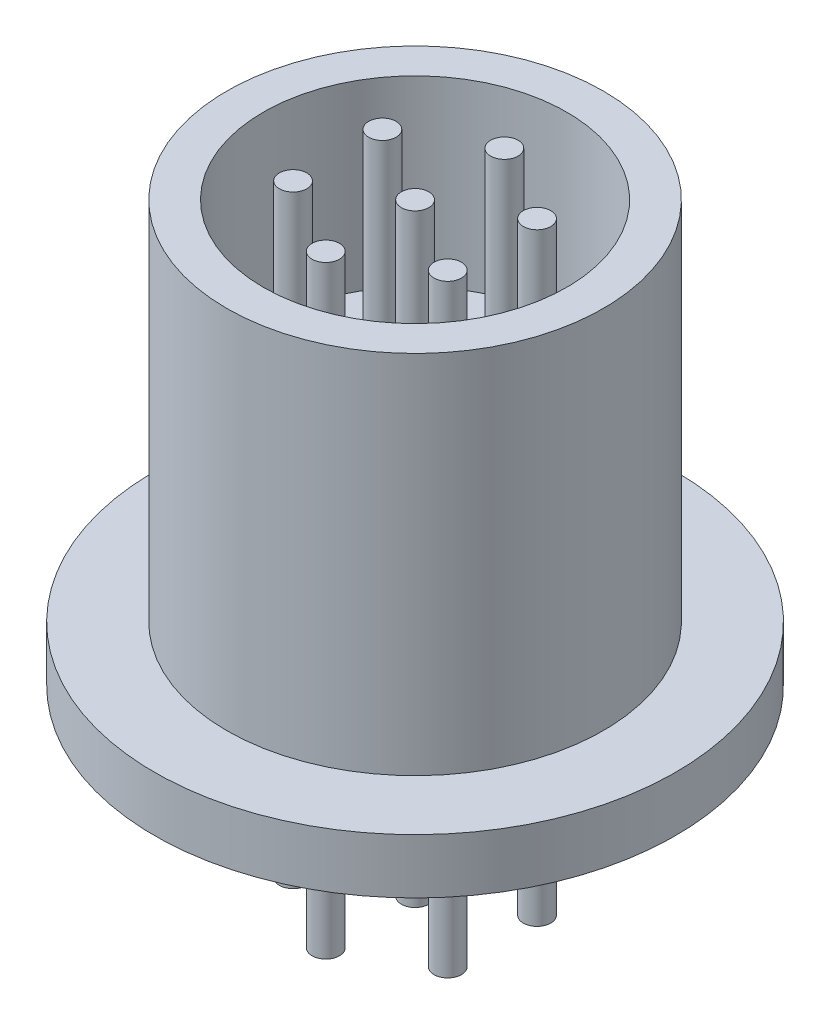
SolidWorks part; units mm, degrees
ref_plane "Front Plane" through (0, 0, 0) normal (0, 0, 1) x (1, 0, 0)
ref_plane "Top Plane" through (0, 0, 0) normal (0, 1, 0) x (1, 0, 0)
ref_plane "Right Plane" through (0, 0, 0) normal (1, 0, 0) x (0, 0, -1)
sketch "Sketch1" plane through (0, 0, 0) normal (0, 1, 0) x (1, 0, 0)
  circle A0 centre (0, 0) radius 10.3
  dimension "D1" = 20.6
extrude "Boss-Extrude1" add sketch "Sketch1" along normal blind 20
sketch "Sketch2" plane through (0, 0, 0) normal (0, -1, 0) x (1, 0, 0)
  circle A0 centre (0, 0) radius 14.25
  dimension "D1" = 28.5
extrude "Boss-Extrude2" add sketch "Sketch2" along normal blind 3
sketch "Sketch3" plane through (0, 20, 0) normal (0, 1, 0) x (1, 0, 0)
  circle A0 centre (0, 0) radius 8.3
  circle A1 centre (0, 0) radius 10.3 construction
  dimension "D1" = 2
extrude "Cut-Extrude1" cut sketch "Sketch3" against normal blind 10
sketch "Sketch4" plane through (0, 10, 0) normal (0, 1, 0) x (1, 0, 0)
  circle A0 centre (0, 4.8844) radius 0.75
  circle A1 centre (4.23, 2.4422) radius 0.75
  circle A2 centre (4.23, -2.4422) radius 0.75
  circle A3 centre (0, -4.8844) radius 0.75
  circle A4 centre (-4.23, -2.4422) radius 0.75
  circle A5 centre (-4.23, 2.4422) radius 0.75
  circle A6 centre (0, 0) radius 0.75
  point P14 (0, 0)
  dimension "D2" = 1.5
  dimension "D1" = 6
extrude "Boss-Extrude3" add sketch "Sketch4" along normal blind 10
sketch "Sketch5" plane through (0, -3, 0) normal (0, -1, 0) x (1, 0, 0)
  circle A1 centre (0, 0) radius 0.75
  circle A2 centre (0, 0) radius 0.75
  circle A3 centre (-4.23, -2.4422) radius 0.75
  circle A4 centre (-4.23, -2.4422) radius 0.75
  circle A5 centre (-4.23, 2.4422) radius 0.75
  circle A6 centre (-4.23, 2.4422) radius 0.75
  circle A7 centre (0, 4.8844) radius 0.75
  circle A8 centre (0, 4.8844) radius 0.75
  circle A9 centre (4.23, 2.4422) radius 0.75
  circle A10 centre (4.23, 2.4422) radius 0.75
  circle A11 centre (4.23, -2.4422) radius 0.75
  circle A12 centre (4.23, -2.4422) radius 0.75
  circle A13 centre (0, -4.8844) radius 0.75
  circle A14 centre (0, -4.8844) radius 0.75
  dimension "D1" = 0
  dimension "D2" = 0
  dimension "D3" = 0
  dimension "D4" = 0
  dimension "D5" = 0
  dimension "D6" = 0
  dimension "D7" = 0
extrude "Boss-Extrude4" add sketch "Sketch5" along normal blind 10
